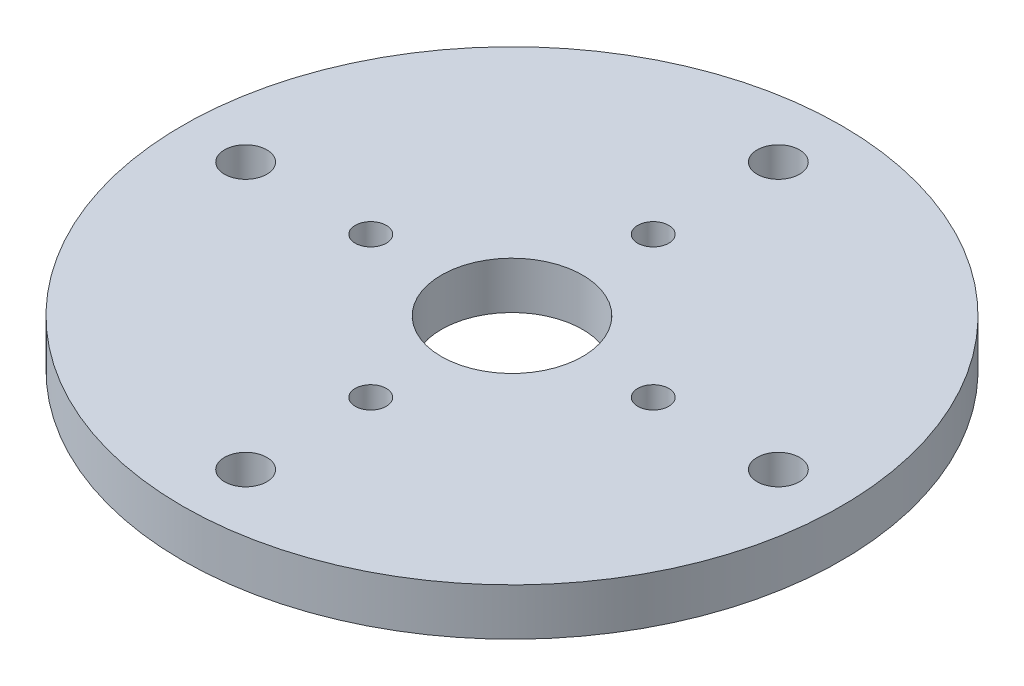
SolidWorks part; units mm, degrees
ref_plane "Front Plane" through (0, 0, 0) normal (0, 0, 1) x (1, 0, 0)
ref_plane "Top Plane" through (0, 0, 0) normal (0, 1, 0) x (1, 0, 0)
ref_plane "Right Plane" through (0, 0, 0) normal (1, 0, 0) x (0, 0, -1)
sketch "Sketch1" plane through (0, 0, 0) normal (0, 1, 0) x (1, 0, 0)
  circle A0 centre (0, 0) radius 35
  dimension "D1" = 70
extrude "Boss-Extrude1" add sketch "Sketch1" along normal blind 5
sketch "Sketch2" plane through (0, 5, 0) normal (0, 1, 0) x (1, 0, 0)
  line L0 (0, -2.75) -> (0, 2.75) construction
  line L1 (-2.75, 0) -> (2.75, 0) construction
  circle A0 centre (0, 28.285) radius 2.25
  dimension "D1" = 4.5
  dimension "D2" = 28.285
extrude "Cut-Extrude1" cut sketch "Sketch2" against normal blind 5
pattern_circular "CirPattern2" count 4 over 360 about axis through (0, 0, 0) along (0, 1, 0) of "Cut-Extrude1"
sketch "Sketch3" plane through (0, 5, 0) normal (0, 1, 0) x (1, 0, 0)
  line L0 (0, -2.75) -> (0, 2.75) construction
  line L1 (-2.75, 0) -> (2.75, 0) construction
  circle A0 centre (0, 15) radius 1.65
  dimension "D1" = 3.3
  dimension "D2" = 15
extrude "Cut-Extrude2" cut sketch "Sketch3" against normal blind 5
pattern_circular "CirPattern3" count 4 over 360 about axis through (0, 0, 0) along (0, 1, 0) of "Cut-Extrude2"
sketch "Sketch4" plane through (0, 5, 0) normal (0, 1, 0) x (1, 0, 0)
  circle A0 centre (0, 0) radius 7.5
  dimension "D1" = 15
extrude "Cut-Extrude3" cut sketch "Sketch4" against normal through all
